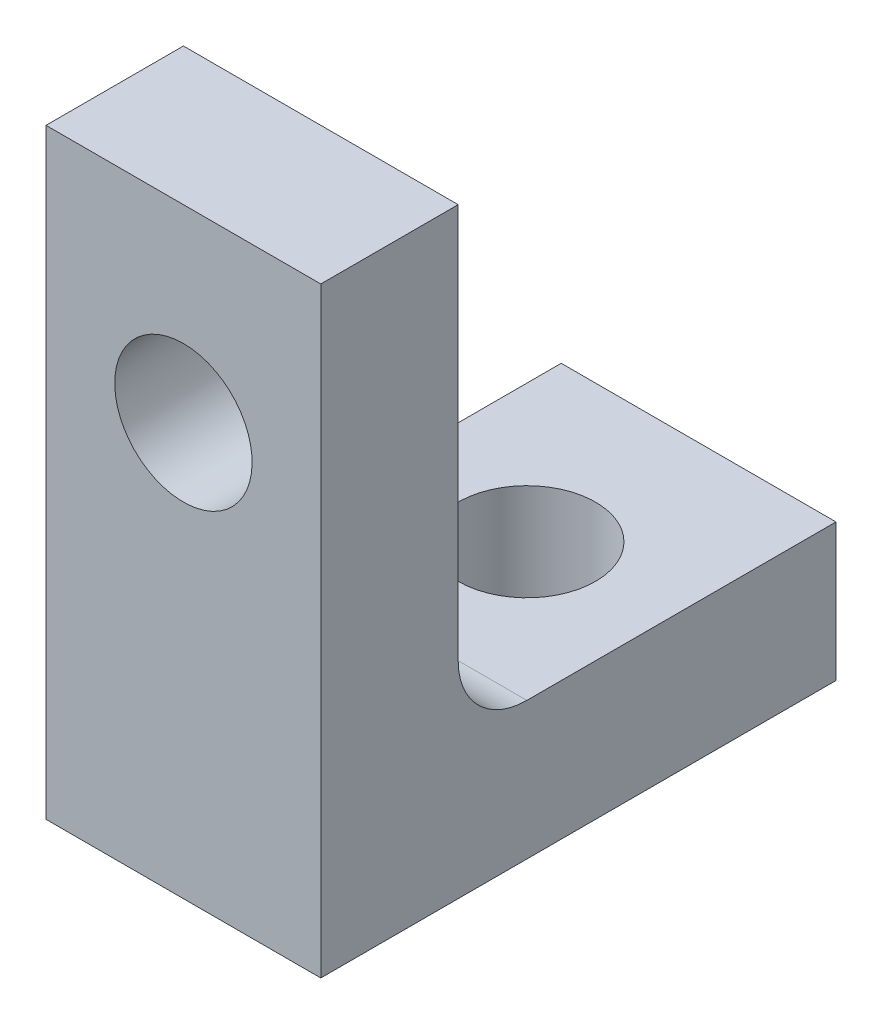
SolidWorks part; units mm, degrees
ref_plane "Front Plane" through (0, 0, 0) normal (0, 0, 1) x (1, 0, 0)
ref_plane "Top Plane" through (0, 0, 0) normal (0, 1, 0) x (1, 0, 0)
ref_plane "Right Plane" through (0, 0, 0) normal (1, 0, 0) x (0, 0, -1)
sketch "Sketch1" plane through (0, 0, 0) normal (1, 0, 0) x (0, 0, -1)
  line L0 (0, 0) -> (0, 6.75)
  line L1 (0, 6.75) -> (-2, 6.75)
  line L2 (-2, 6.75) -> (-2, -2)
  line L3 (-2, -2) -> (5.5, -2)
  line L4 (5.5, -2) -> (5.5, 0)
  line L5 (5.5, 0) -> (0, 0)
  dimension "D1" = 2
  dimension "D2" = 2
  dimension "D3" = 8.75
  dimension "D4" = 7.5
extrude "Boss-Extrude1" add sketch "Sketch1" along normal blind 4
sketch "Sketch2" plane through (0, 0, 0) normal (0, 0, -1) x (-1, 0, 0)
  line L0 (-2, 6.75) -> (-2, -2) construction
  line L1 (-4, 6.75) -> (0, 6.75) construction
  line L2 (-4, -2) -> (0, -2) construction
  circle A0 centre (-2, 4) radius 1
  dimension "D1" = 2
  dimension "D2" = 6
extrude "Cut-Extrude1" cut sketch "Sketch2" against normal through all
sketch "Sketch3" plane through (0, 0, 0) normal (0, 1, 0) x (1, 0, 0)
  line L0 (2, 5.5) -> (2, -2) construction
  line L1 (4, 5.5) -> (0, 5.5) construction
  line L2 (4, -2) -> (0, -2) construction
  circle A0 centre (2, 3) radius 1
  dimension "D1" = 2
  dimension "D2" = 5
extrude "Cut-Extrude2" cut sketch "Sketch3" against normal through all
fillet "Fillet1" radius 1 1 edges at (2, 0, 0)
